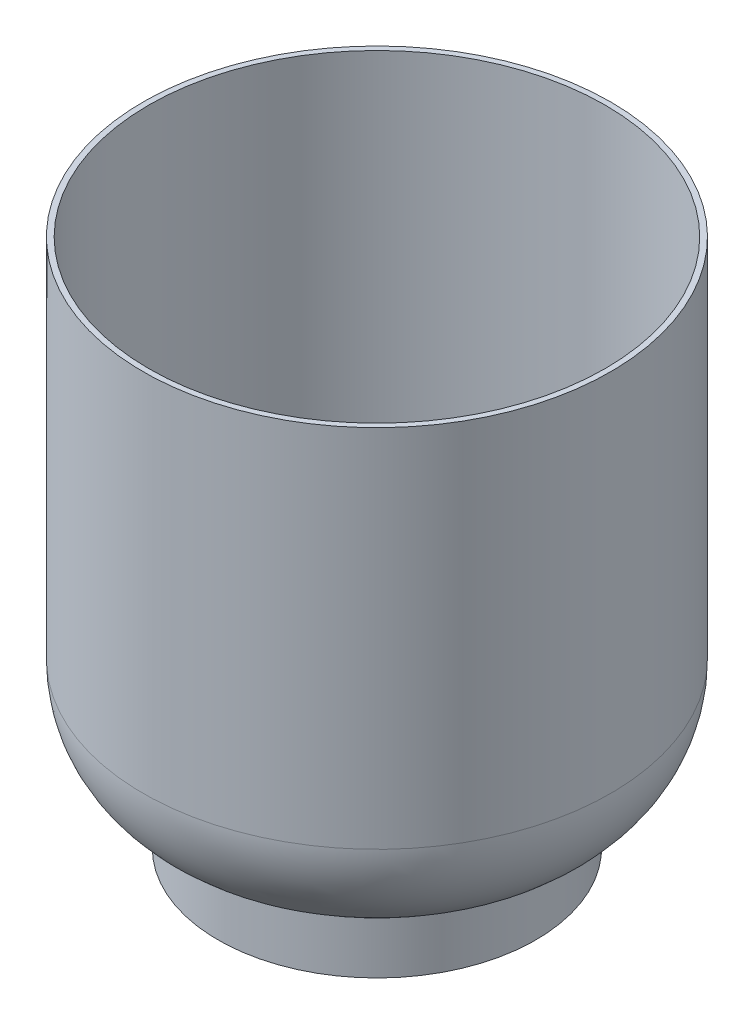
SolidWorks part; units mm, degrees
ref_plane "Ön Düzlem" through (0, 0, 0) normal (0, 0, 1) x (1, 0, 0)
ref_plane "Üst Düzlem" through (0, 0, 0) normal (0, 1, 0) x (1, 0, 0)
ref_plane "Sağ Düzlem" through (0, 0, 0) normal (1, 0, 0) x (0, 0, -1)
sketch "Çizim1" plane through (0, 0, 0) normal (0, 0, 1) x (1, 0, 0)
  line L0 (0, 0) -> (0, 200) construction
  line L1 (-62.5, 208.7141) -> (-62.5, 108.7141)
  line L2 (-42, 79.1971) -> (-42, 63.7141)
  line L3 (-64, 208.7141) -> (-64, 108.7141)
  line L4 (-43.5, 78.1731) -> (-43.5, 63.7141)
  line L5 (-42, 63.7141) -> (-43.5, 63.7141)
  line L6 (-62.5, 208.7141) -> (-64, 208.7141)
  line L7 (-42, 69.7141) -> (-36, 69.7141)
  line L8 (-36, 69.7141) -> (-36, 73.7141)
  line L9 (-36, 73.7141) -> (-42, 73.7141)
  line L10 (-43.5, 79.1971) -> (-43.5, 63.7141) construction
  line L11 (-42, 80.258) -> (-42, 63.7141) construction
  arc A0 (-62.5, 108.7141) -> (-42.9762, 80.6027) centre (-32.5, 108.7141) ccw
  arc A1 (-64, 108.7141) -> (-44.4318, 79.5613) centre (-32.5, 108.7141) ccw
  arc A2 (-64, 108.7141) -> (-43.5, 79.1971) centre (-32.5, 108.7141) ccw construction
  arc A3 (-44.4318, 79.5613) -> (-43.5, 78.1731) centre (-45, 78.1731) cw
  arc A4 (-62.5, 108.7141) -> (-42, 80.258) centre (-32.5, 108.7141) ccw construction
  arc A5 (-42, 79.1971) -> (-42.9762, 80.6027) centre (-43.5, 79.1971) ccw
  point P17 (0, 0)
  point P24 (-42, 80.258)
  dimension "D7" = 60
  dimension "D13" = 1.5
  dimension "D1" = 200
  dimension "D2" = 100
  dimension "D3" = 62.5
  dimension "D4" = 16.5439
  dimension "D5" = 42
  dimension "D6" = 145
  dimension "D8" = 32.5
  dimension "D10" = 6
  dimension "D11" = 4
  dimension "D12" = 10
  dimension "D9" = 1.5
revolve "Döndür1" add sketch "Çizim1" angle 360 about L0
